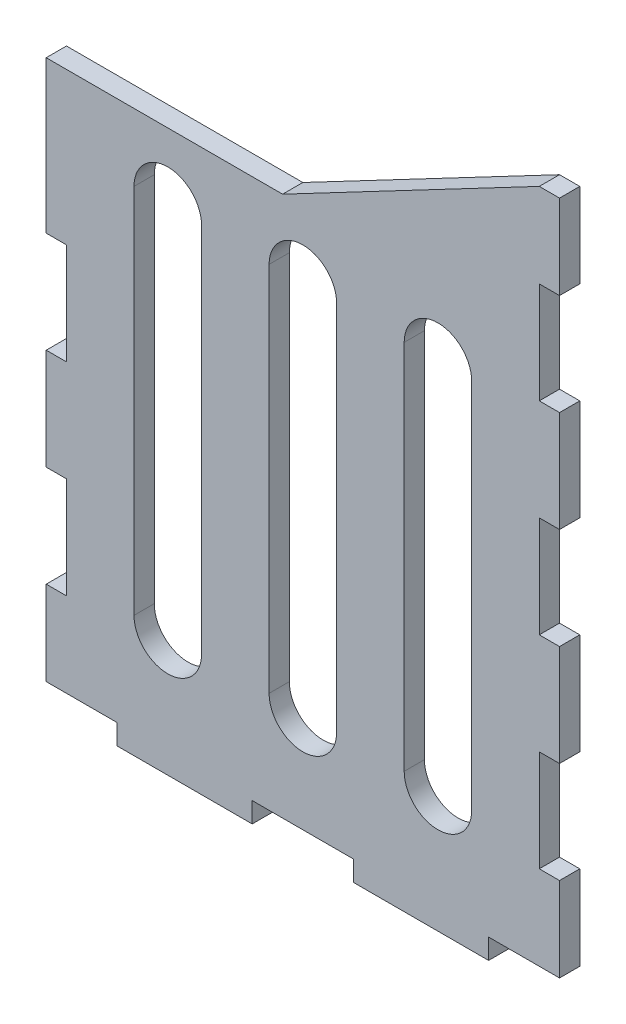
SolidWorks part; units mm, degrees
ref_plane "Front Plane" through (0, 0, 0) normal (0, 0, 1) x (1, 0, 0)
ref_plane "Top Plane" through (0, 0, 0) normal (0, 1, 0) x (1, 0, 0)
ref_plane "Right Plane" through (0, 0, 0) normal (1, 0, 0) x (0, 0, -1)
sketch "Sketch1" plane through (0, 0, 0) normal (0, 0, 1) x (1, 0, 0)
  line L0 (-3, 30) -> (35, 50)
  line L1 (38, -50) -> (-38, -50)
  line L2 (38, -50) -> (38, 50)
  line L3 (38, 50) -> (-38, 50)
  line L4 (-38, -50) -> (-38, 50)
  line L5 (38, -50) -> (-38, 50) construction
  line L6 (38, 50) -> (-38, -50) construction
  line L7 (-38, 30) -> (-3, 30)
  line L8 (35, 22.5) -> (38, 22.5)
  line L9 (35, 22.5) -> (35, 37.5)
  line L10 (35, 37.5) -> (38, 37.5)
  line L11 (38, 22.5) -> (38, 37.5)
  line L12 (35, 22.5) -> (38, 37.5) construction
  line L13 (35, 37.5) -> (38, 22.5) construction
  line L14 (35, -7.5) -> (38, -7.5)
  line L15 (35, -7.5) -> (35, 7.5)
  line L16 (35, 7.5) -> (38, 7.5)
  line L17 (38, -7.5) -> (38, 7.5)
  line L18 (35, -7.5) -> (38, 7.5) construction
  line L19 (35, 7.5) -> (38, -7.5) construction
  line L24 (0, -55) -> (0, 55) construction
  line L25 (-35, -22.5) -> (-38, -22.5)
  line L26 (27.5, -53) -> (7.5, -53)
  line L27 (27.5, -53) -> (27.5, -50)
  line L28 (27.5, -50) -> (7.5, -50)
  line L29 (7.5, -53) -> (7.5, -50)
  line L30 (27.5, -53) -> (7.5, -50) construction
  line L31 (27.5, -50) -> (7.5, -53) construction
  line L32 (-7.5, -53) -> (-27.5, -53)
  line L33 (-7.5, -53) -> (-7.5, -50)
  line L34 (-7.5, -50) -> (-27.5, -50)
  line L35 (-27.5, -53) -> (-27.5, -50)
  line L36 (-7.5, -53) -> (-27.5, -50) construction
  line L37 (-7.5, -50) -> (-27.5, -53) construction
  line L38 (35, -37.5) -> (38, -37.5)
  line L39 (35, -37.5) -> (35, -22.5)
  line L40 (35, -22.5) -> (38, -22.5)
  line L41 (38, -37.5) -> (38, -22.5)
  line L42 (35, -37.5) -> (38, -22.5) construction
  line L43 (35, -22.5) -> (38, -37.5) construction
  line L48 (-38, -37.5) -> (-38, -22.5)
  line L49 (-35, -37.5) -> (-38, -37.5)
  line L50 (-35, -37.5) -> (-35, -22.5)
  line L53 (0, -35) -> (0, 20) construction
  line L56 (-35, 7.5) -> (-38, 7.5)
  line L59 (-38, -7.5) -> (-38, 7.5)
  line L60 (-35, -7.5) -> (-38, -7.5)
  line L61 (-35, -7.5) -> (-35, 7.5)
  line L66 (-5, -35) -> (-5, 20)
  line L69 (5, -35) -> (5, 20)
  line L72 (20, -35) -> (20, 20) construction
  line L73 (15, -35) -> (15, 20)
  line L74 (25, -35) -> (25, 20)
  line L75 (-20, -35) -> (-20, 20) construction
  line L76 (-15, -35) -> (-15, 20)
  line L77 (-25, -35) -> (-25, 20)
  arc A10 (-5, -35) -> (5, -35) centre (0, -35) ccw
  arc A11 (5, 20) -> (-5, 20) centre (0, 20) ccw
  arc A12 (15, -35) -> (25, -35) centre (20, -35) ccw
  arc A13 (25, 20) -> (15, 20) centre (20, 20) ccw
  arc A14 (-15, -35) -> (-25, -35) centre (-20, -35) cw
  arc A15 (-25, 20) -> (-15, 20) centre (-20, 20) cw
  point P0 (0, 0)
  point P8 (36.5, 30)
  point P13 (36.5, 0)
  point P23 (17.5, -51.5)
  point P28 (-17.5, -51.5)
  point P34 (36.5, -30)
  point P42 (0, -7.5)
  point P51 (20, -7.5)
  point P58 (0, 0)
  point P59 (0, 0)
  point P62 (-20, -7.5)
  dimension "D17" = 10
  dimension "D10" = 5
  dimension "D1" = 76
  dimension "D2" = 100
  dimension "D3" = 3
  dimension "D4" = 80
  dimension "D5" = 3
  dimension "D6" = 15
  dimension "D7" = 15
  dimension "D8" = 15
  dimension "D9" = 35
  dimension "D11" = 55
  dimension "D12" = 3
  dimension "D13" = 20
  dimension "D14" = 15
  dimension "D15" = 7.5
  dimension "D16" = 7.5
extrude "Boss-Extrude1" add sketch "Sketch1" along normal blind 3
